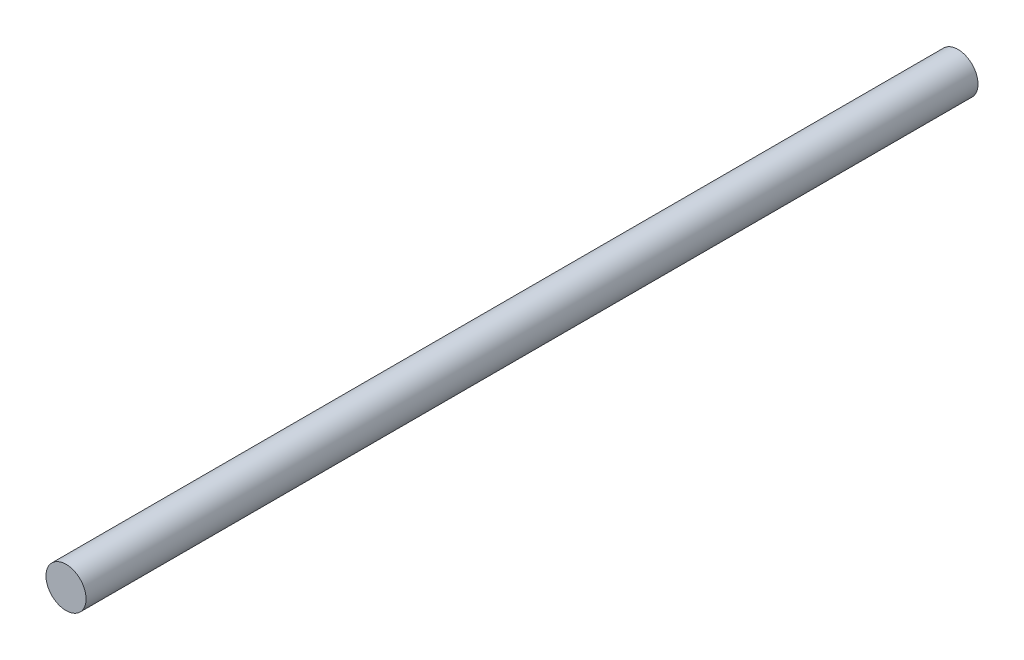
SolidWorks part; units mm, degrees
ref_plane "Piano frontale" through (0, 0, 0) normal (0, 0, 1) x (1, 0, 0)
ref_plane "Piano superiore" through (0, 0, 0) normal (0, 1, 0) x (1, 0, 0)
ref_plane "Piano destro" through (0, 0, 0) normal (1, 0, 0) x (0, 0, -1)
sketch "Schizzo1" plane through (0, 0, 0) normal (0, 0, 1) x (1, 0, 0)
  line L0 (0, 0) -> (0, 38.2658) construction
  circle A1 centre (0, 0) radius 9
  dimension "D1" = 18
extrude "Estrusione-Estrusione1" add sketch "Schizzo1" along normal blind 400
ref_plane "Piano4" through (0, 0, 200) normal (0, 0, 1) x (1, 0, 0)
